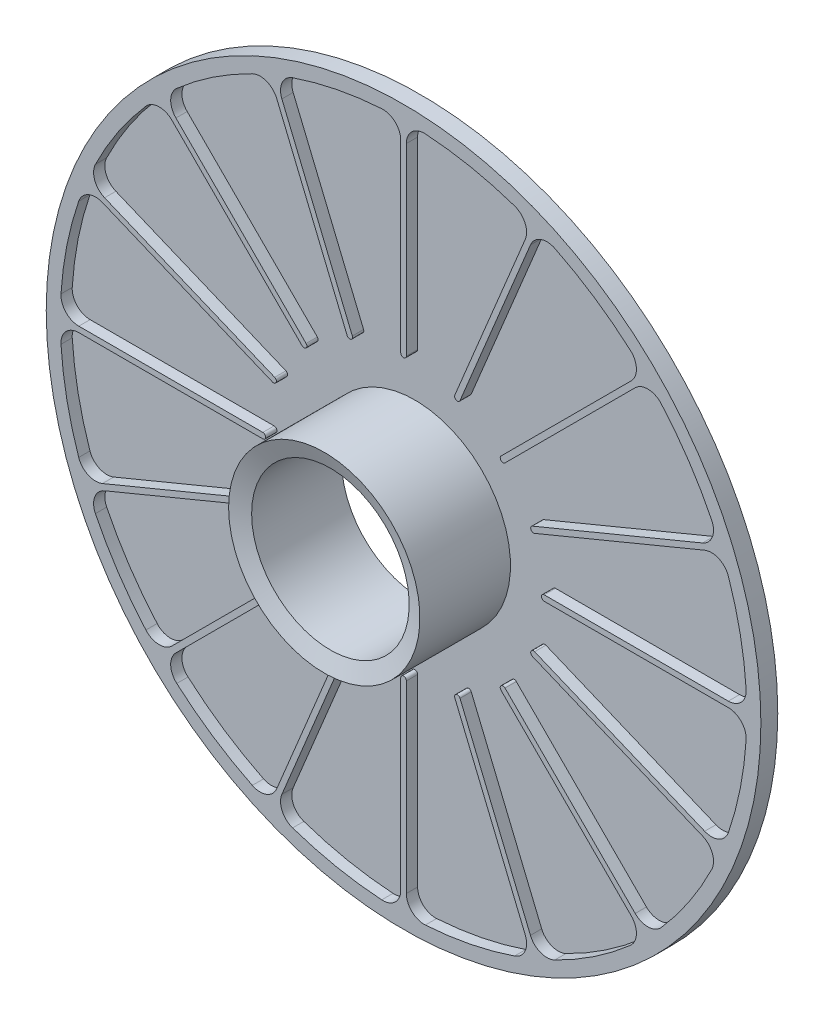
SolidWorks part; units mm, degrees
ref_plane "Front Plane" through (0, 0, 0) normal (1, 0, 0) x (0, 1, 0)
ref_plane "Top Plane" through (0, 0, 0) normal (0, 0, 1) x (0, 1, 0)
ref_plane "Right Plane" through (0, 0, 0) normal (0, 1, 0) x (-1, 0, 0)
sketch "Sketch1" plane through (0, 0, 0) normal (1, 0, 0) x (0, 1, 0)
  line L0 (14, 0) -> (14, 16)
  line L1 (14, 16) -> (17, 17.0919)
  line L2 (17, 17.0919) -> (17, 1)
  line L3 (17, 1) -> (63.5, 1)
  line L4 (63.5, 1) -> (63.5, 0)
  line L7 (63.5, 0) -> (14, 0)
  line L8 (0, 0) -> (0, 22.7488) construction
  line L9 (36, 0) -> (36, -15) construction
  point P7 (0, 0)
  point P13 (55, -27.7795)
  point P14 (0, 0)
  dimension "D1" = 28
  dimension "D2" = 16
  dimension "D3" = 1
  dimension "D4" = 3
  dimension "D5" = 70
  dimension "D6" = 36
  dimension "D7" = 63.5
  dimension "D9" = 15
revolve "Revolve1" add sketch "Sketch1" angle 360 about L8
sketch "Sketch2" plane through (0, 0, 1) normal (0, 0, 1) x (1, 0, 0)
  line L0 (-0.5, 25) -> (-0.5, 60.998)
  line L1 (0.5, 60.998) -> (0.5, 25)
  line L2 (0, 0) -> (0, 61) construction
  arc A1 (0.5, 25) -> (-0.5, 25) centre (0, 25) cw
  circle A2 centre (0, 0) radius 61
  circle A3 centre (0, 0) radius 63.5
  arc A4 (-3.8768, 60.8767) -> (-0.5, 57.7081) centre (-3.675, 57.7081) cw
  arc A5 (3.8768, 60.8767) -> (0.5, 57.7081) centre (3.675, 57.7081) ccw
  point P13 (0, 0)
  point P14 (0, 0)
  circle M5 centre (0, 0) radius 63.5
  dimension "D1" = 1
  dimension "D4" = 122
  dimension "D2" = 3.175
  dimension "D3" = 25
extrude "Boss-Extrude1" add sketch "Sketch2" along normal blind 2 contours L2 A1 L1 A2 | A5 A2 L1 | A2 A4 L0 | A1 L2 A2 L0 | A2 M5
pattern_circular "CirPattern1" count 16 over 360 about axis through (0, 0, 0) along (0, 0, 1) of "Boss-Extrude1"
